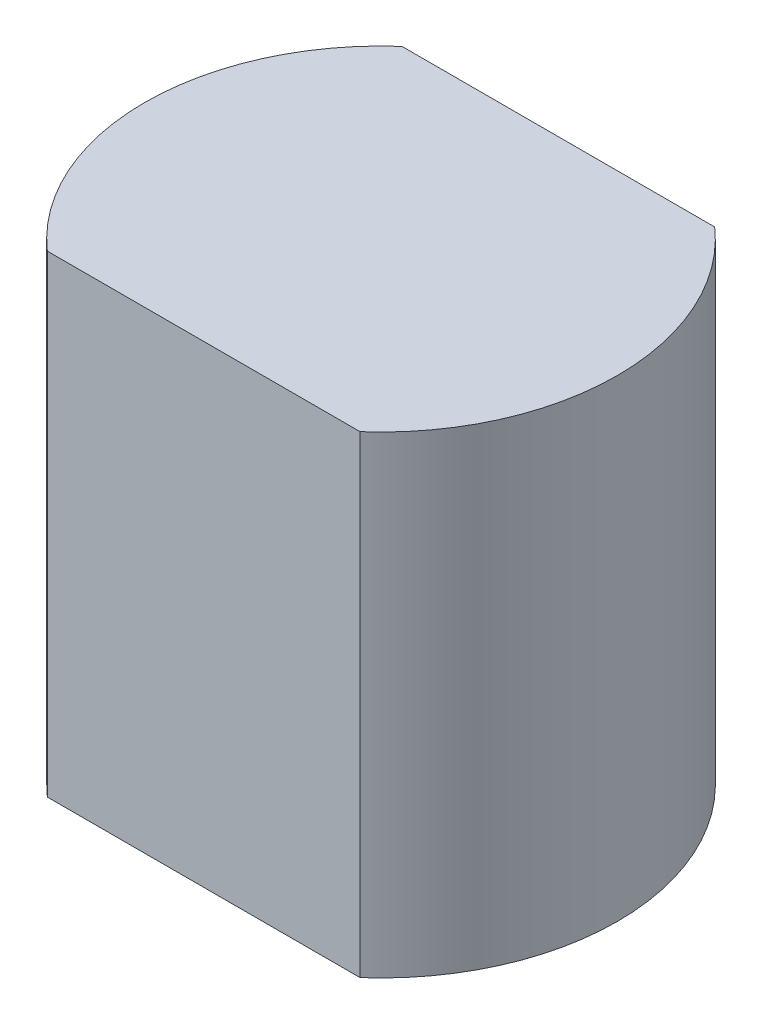
SolidWorks part; units mm, degrees
material "AISI 316 Annealed Stainless Steel Bar (SS)"
ref_plane "Front Plane" through (0, 0, 0) normal (0, 0, 1) x (1, 0, 0)
ref_plane "Top Plane" through (0, 0, 0) normal (0, 1, 0) x (1, 0, 0)
ref_plane "Right Plane" through (0, 0, 0) normal (1, 0, 0) x (0, 0, -1)
sketch "Sketch1" plane through (0, 0, 0) normal (0, 1, 0) x (1, 0, 0)
  line L0 (8.4003, 9.525) -> (-8.4003, 9.525)
  line L1 (-8.4003, -9.525) -> (8.4003, -9.525)
  line L2 (-12.7, 0) -> (12.7, 0) construction
  arc A0 (-8.4003, 9.525) -> (-8.4003, -9.525) centre (0, 0) ccw
  arc A1 (8.4003, -9.525) -> (8.4003, 9.525) centre (0, 0) ccw
  dimension "D1" = 25.4
  dimension "D2" = 19.05
extrude "Boss-Extrude1" add sketch "Sketch1" along normal blind 25.4
sketch "Sketch2" plane through (0, 0, -9.525) normal (0, 0, -1) x (-1, 0, 0)
  text T0 "Motor"
extrude "Cut-Extrude1" cut sketch "Sketch2" against normal blind 0.7937
